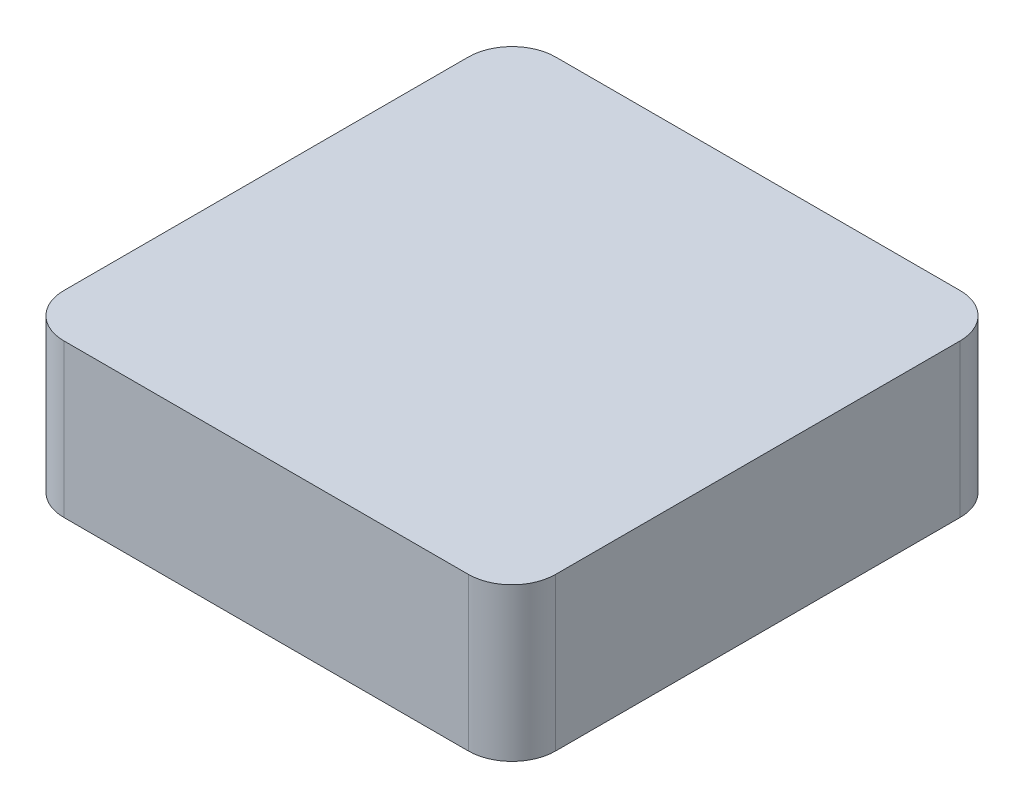
SolidWorks part; units mm, degrees
ref_plane "Front Plane" through (0, 0, 0) normal (0, 0, 1) x (1, 0, 0)
ref_plane "Top Plane" through (0, 0, 0) normal (0, 1, 0) x (1, 0, 0)
ref_plane "Right Plane" through (0, 0, 0) normal (1, 0, 0) x (0, 0, -1)
sketch "Sketch1" plane through (0, 0, 0) normal (0, 1, 0) x (1, 0, 0)
  line L1 (-22.5, -22.5) -> (22.5, -22.5)
  line L2 (-22.5, -22.5) -> (-22.5, 22.5)
  line L3 (-22.5, 22.5) -> (22.5, 22.5)
  line L4 (22.5, -22.5) -> (22.5, 22.5)
  line L5 (-22.5, -22.5) -> (22.5, 22.5) construction
  line L6 (-22.5, 22.5) -> (22.5, -22.5) construction
  point P0 (0, 0)
  dimension "D1" = 45
  dimension "D2" = 45
extrude "Boss-Extrude1" add sketch "Sketch1" along normal mid plane 14
fillet "Fillet1" radius 4 4 edges at (-22.5, 0, -22.5) (22.5, 0, -22.5) (22.5, 0, 22.5) (-22.5, 0, 22.5)
